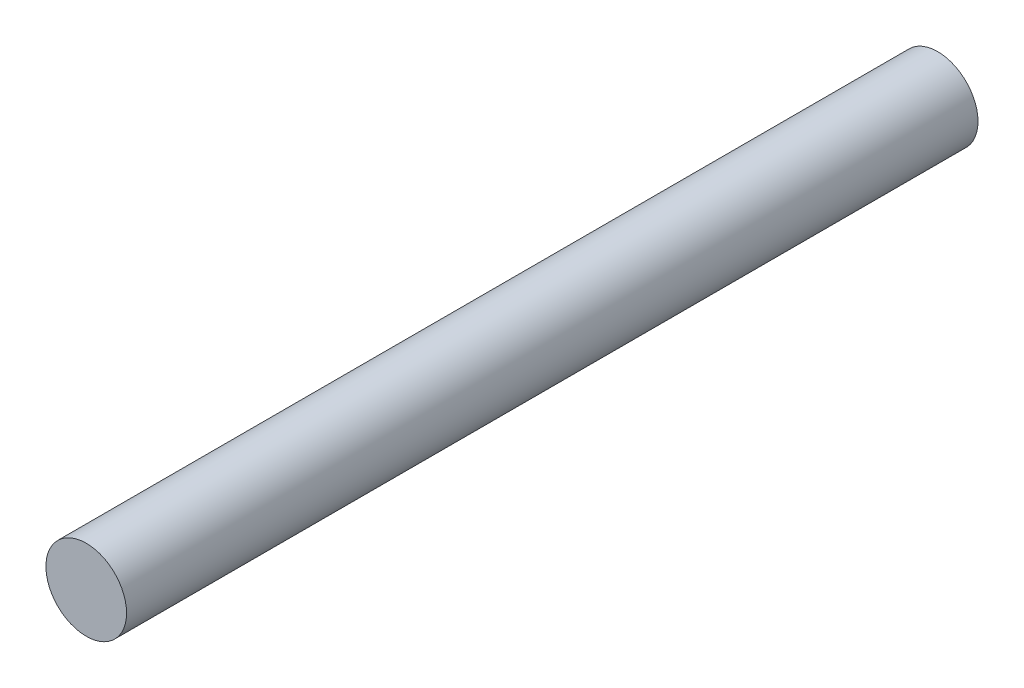
SolidWorks part; units mm, degrees
material "ABS"
ref_plane "Front Plane" through (0, 0, 0) normal (0, 0, 1) x (1, 0, 0)
ref_plane "Top Plane" through (0, 0, 0) normal (0, 1, 0) x (1, 0, 0)
ref_plane "Right Plane" through (0, 0, 0) normal (1, 0, 0) x (0, 0, -1)
sketch "Sketch1" plane through (0, 0, 0) normal (0, 0, 1) x (1, 0, 0)
  circle A0 centre (0, 0) radius 1.5875
extrude "Boss-Extrude1" add sketch "Sketch1" along normal blind 33.528
